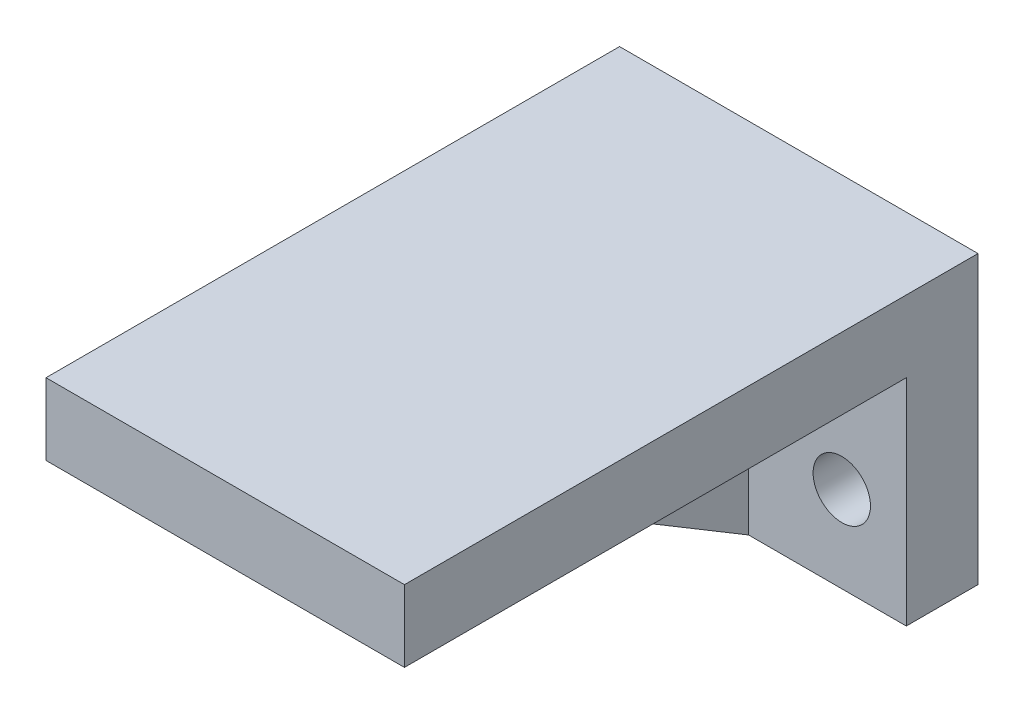
SolidWorks part; units mm, degrees
material "3D printed plastic"
ref_plane "Front Plane" through (0, 0, 0) normal (0, 0, 1) x (1, 0, 0)
ref_plane "Top Plane" through (0, 0, 0) normal (0, 1, 0) x (1, 0, 0)
ref_plane "Right Plane" through (0, 0, 0) normal (1, 0, 0) x (0, 0, -1)
sketch "Sketch1" plane through (0, 0, 0) normal (1, 0, 0) x (0, 0, -1)
  line L1 (0, 0) -> (-40, 0)
  line L2 (0, 0) -> (0, -20)
  line L3 (0, -20) -> (-5, -20)
  line L4 (-40, 0) -> (-40, -5)
  line L7 (-40, -5) -> (-5, -5)
  line L8 (-5, -20) -> (-5, -5)
  dimension "D1" = 5
  dimension "D2" = 40
  dimension "D3" = 5
  dimension "D4" = 20
extrude "Boss-Extrude1" add sketch "Sketch1" along normal mid plane 25
sketch "Sketch2" plane through (0, 0, 0) normal (1, 0, 0) x (0, 0, -1)
  line L1 (-30, -5) -> (-5, -20)
  line L2 (-5, -20) -> (-5, -5)
  line L3 (-5, -5) -> (-30, -5)
  line L4 (-40, -5) -> (-5, -5) construction
  line L5 (-40, 0) -> (-40, -5) construction
  dimension "D1" = 10
extrude "Boss-Extrude2" add sketch "Sketch2" along normal mid plane 3
sketch "Sketch3" plane through (0, 0, 5) normal (0, 0, 1) x (1, 0, 0)
  line L0 (-8, -14) -> (8, -14) construction
  line L1 (0, -14) -> (0, 0) construction
  line L2 (12.5, -5) -> (1.5, -5) construction
  circle A0 centre (8, -14) radius 2
  circle A1 centre (-8, -14) radius 2
  dimension "D1" = 16
  dimension "D3" = 4
  dimension "D2" = 9
extrude "Cut-Extrude1" cut sketch "Sketch3" against normal through all
